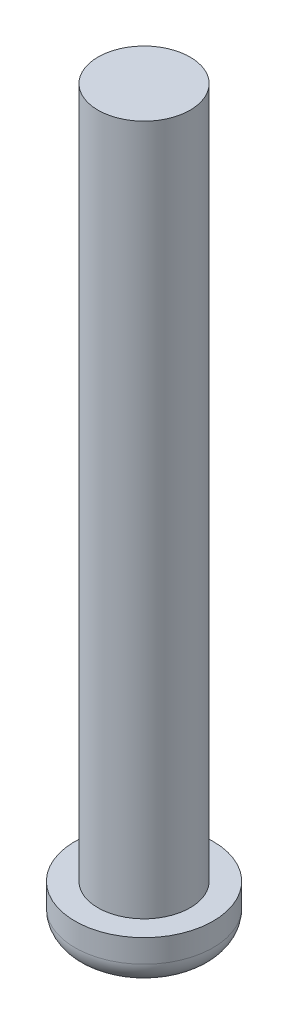
SolidWorks part; units mm, degrees
ref_plane "Alzado" through (0, 0, 0) normal (0, 0, 1) x (1, 0, 0)
ref_plane "Planta" through (0, 0, 0) normal (0, 1, 0) x (1, 0, 0)
ref_plane "Vista lateral" through (0, 0, 0) normal (1, 0, 0) x (0, 0, -1)
sketch "Croquis1" plane through (0, 0, 0) normal (0, 1, 0) x (1, 0, 0)
  circle A0 centre (0, 0) radius 4
  dimension "D1" = 8
extrude "Saliente-Extruir1" add sketch "Croquis1" along normal blind 60
sketch "Croquis2" plane through (0, 0, 0) normal (0, -1, 0) x (-1, 0, 0)
  circle A0 centre (0, 0) radius 6
extrude "Saliente-Extruir2" add sketch "Croquis2" along normal blind 4
fillet "Redondeo1" radius 2 1 edges at (0, -4, -6)
